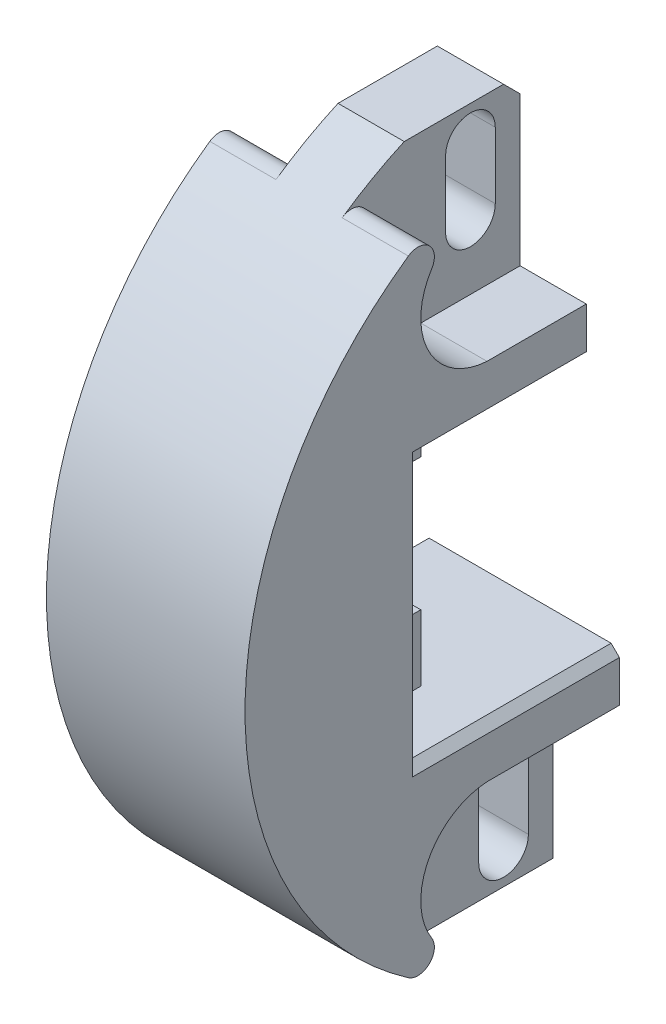
SolidWorks part; units mm, degrees
ref_plane "Front Plane" through (0, 0, 0) normal (1, 0, 0) x (0, 1, 0)
ref_plane "Top Plane" through (0, 0, 0) normal (0, 0, 1) x (0, 1, 0)
ref_plane "Right Plane" through (0, 0, 0) normal (0, 1, 0) x (-1, 0, 0)
sketch "Sketch1" plane through (0, 0, 0) normal (1, 0, 0) x (0, 1, 0)
  line L0 (0, 0) -> (8730.3287, 0) construction
  line L1 (0, 0) -> (0, 8730.3287) construction
  line L2 (-21, 0) -> (-21, -9)
  line L3 (-21, -9) -> (-8, -9)
  line L4 (-8, -9) -> (-8, 3)
  line L5 (-8, 3) -> (8, 3)
  line L6 (8, 3) -> (8, -7)
  line L7 (8, -7) -> (21, -7)
  line L8 (21, -7) -> (21, 0)
  arc A1 (21, 0) -> (-21, 0) centre (0, -9.3808) ccw
  point P16 (0, 3)
  dimension "D6" = 46
  dimension "D1" = 7
  dimension "D2" = 10
  dimension "D3" = 42
  dimension "D4" = 2
  dimension "D5" = 16
extrude "Boss-Extrude1" add sketch "Sketch1" along normal mid plane 12
chamfer "Chamfer1" distance 0.5 angle 45 3 edges at (6, 8, -2) (6, 0, 3) (6, -8, -3)
chamfer "Chamfer2" distance 0.5 angle 45 3 edges at (-6, 8, -2) (-6, 0, 3) (-6, -8, -3)
sketch "Sketch3" plane through (0, 0, 0) normal (1, 0, 0) x (0, 1, 0)
  line L1 (-8, 3) -> (-4, 3)
  line L2 (-8, 3) -> (-8, -1)
  line L3 (-8, -1) -> (-4, -1)
  line L4 (-4, 3) -> (-4, -1)
  dimension "D1" = 4
  dimension "D2" = 4
extrude "Boss-Extrude2" add sketch "Sketch3" along normal mid plane 4
mirror "Mirror1" about plane through (0, 0, 0) normal (0, 1, 0) of "Boss-Extrude2"
sketch "Sketch4" plane through (6, 0, 0) normal (1, 0, 0) x (0, 1, 0)
  line L0 (-11, -9) -> (-11, -1)
  line L1 (-21, -9) -> (-8.5, -9) construction
  line L2 (-8, -1) -> (-4, -1) construction
  line L3 (-21, 0) -> (-21, -9) construction
  line L4 (8, 3) -> (-8, 3) construction
  line L5 (-11, -9) -> (-21, -9)
  line L6 (-21, -9) -> (-21, 0)
  line L7 (0, 0) -> (0, 14.8767) construction
  line L8 (21, -7) -> (21, 0)
  line L9 (21, -7) -> (11, -7)
  line L10 (11, -7) -> (11, -1)
  line L11 (8.5, -7) -> (21, -7) construction
  arc A0 (-11, -1) -> (-17.5258, 2.3346) centre (-15.2426, -1.25) ccw
  arc A1 (-18.8841, 3.7489) -> (-17.5258, 2.3346) centre (-18.0631, 3.1781) ccw
  arc A2 (-21, 0) -> (-18.8841, 3.7489) centre (0, -9.3808) cw
  arc A3 (11, -1) -> (17.5258, 2.3346) centre (15.2426, -1.25) cw
  arc A4 (18.8841, 3.7489) -> (17.5258, 2.3346) centre (18.0631, 3.1781) cw
  arc A5 (21, 0) -> (18.8841, 3.7489) centre (0, -9.3808) ccw
  point P4 (-15.2426, 3)
  point P21 (-12, -1.5)
  point P26 (-12, -1.5)
  point P38 (0, 0)
  point P39 (-12, -0.8809)
  dimension "D2" = 8.5
  dimension "D3" = 2
  dimension "D4" = 23
  dimension "D1" = 10
extrude "Cut-Extrude1" cut sketch "Sketch4" against normal blind 4 and the other way through all
mirror "Mirror2" about plane through (0, 0, 0) normal (1, 0, 0) of "Cut-Extrude1"
chamfer "Chamfer3" distance 1 angle 45 1 edges at (0, 21, -7)
sketch "Sketch5" plane through (2, 0, 0) normal (1, 0, 0) x (0, 1, 0)
  line L0 (-19, -6) -> (-15, -6) construction
  line L1 (-19, -4.5) -> (-15, -4.5)
  line L2 (-19, -7.5) -> (-15, -7.5)
  line L3 (-21, -9) -> (-11, -9) construction
  line L5 (-21, 0) -> (-21, -9) construction
  arc A0 (-19, -4.5) -> (-19, -7.5) centre (-19, -6) ccw
  arc A1 (-15, -7.5) -> (-15, -4.5) centre (-15, -6) ccw
  point P2 (-17, -6)
  dimension "D2" = 3
  dimension "D4" = 2
  dimension "D1" = 4
  dimension "D3" = 3
extrude "Cut-Extrude2" cut sketch "Sketch5" against normal through all both and the other way through all
sketch "Sketch6" plane through (2, 0, 0) normal (1, 0, 0) x (0, 1, 0)
  line L0 (19, -4) -> (15, -4) construction
  line L1 (19, -5.5) -> (15, -5.5)
  line L2 (19, -2.5) -> (15, -2.5)
  line L3 (21, -6) -> (21, 0) construction
  line L4 (11, -7) -> (20, -7) construction
  arc A0 (19, -5.5) -> (19, -2.5) centre (19, -4) ccw
  arc A1 (15, -2.5) -> (15, -5.5) centre (15, -4) ccw
  point P2 (17, -4)
  dimension "D1" = 2
  dimension "D2" = 3
  dimension "D3" = 4
  dimension "D4" = 3
extrude "Cut-Extrude3" cut sketch "Sketch6" against normal through all both and the other way through all
